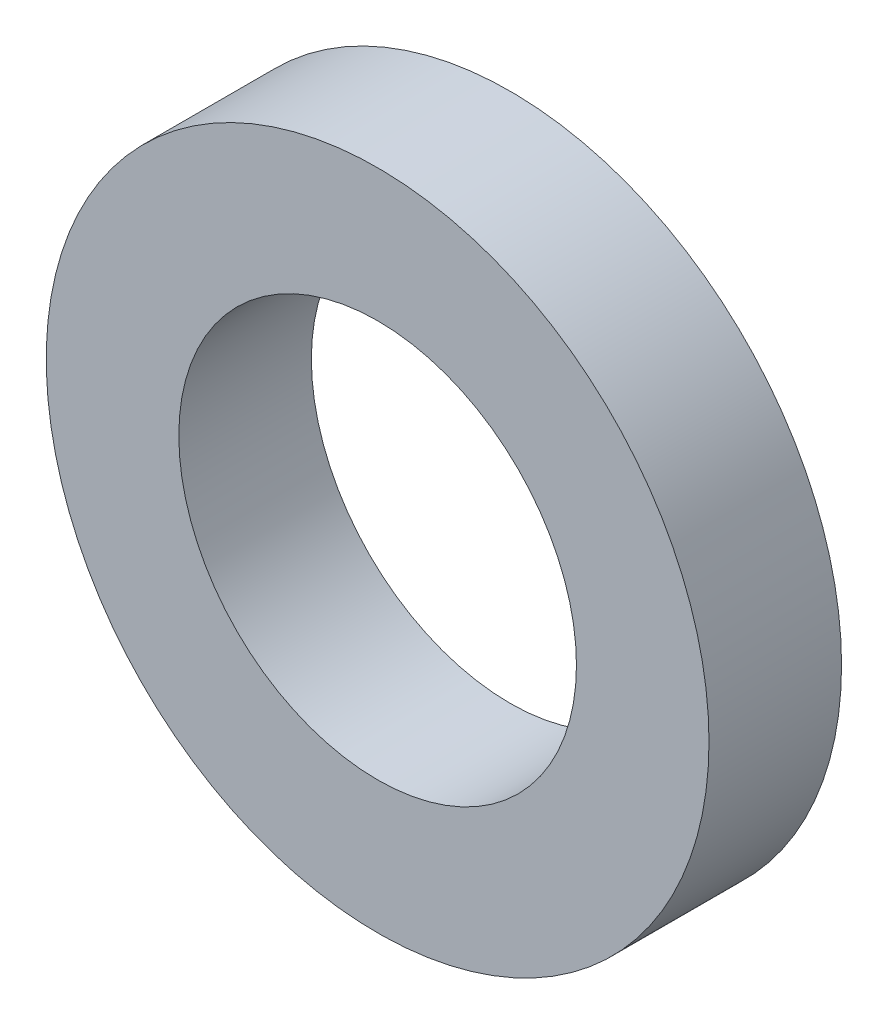
SolidWorks part; units mm, degrees
ref_plane "前视基准面" through (0, 0, 0) normal (0, 0, 1) x (1, 0, 0)
ref_plane "上视基准面" through (0, 0, 0) normal (0, 1, 0) x (1, 0, 0)
ref_plane "右视基准面" through (0, 0, 0) normal (1, 0, 0) x (0, 0, -1)
sketch "草图1" plane through (0, 0, 0) normal (0, 0, 1) x (1, 0, 0)
  circle A0 centre (0, 0) radius 1.5
  circle A1 centre (0, 0) radius 2.5
extrude "凸台-拉伸1" add sketch "草图1" along normal blind 1
